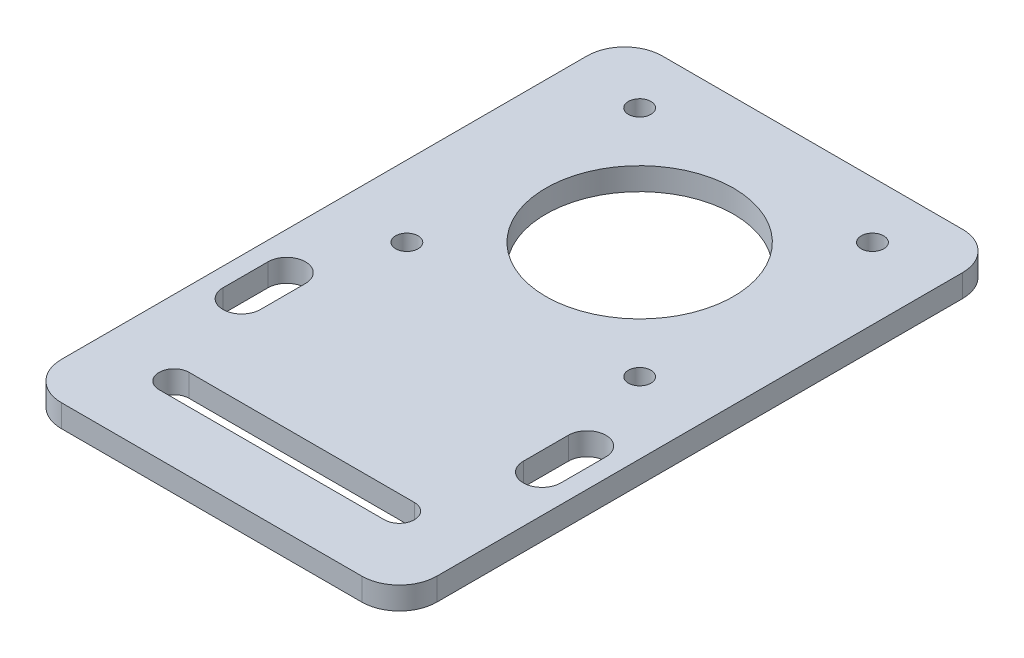
SolidWorks part; units mm, degrees
ref_plane "Front Plane" through (0, 0, 0) normal (0, 0, 1) x (1, 0, 0)
ref_plane "Top Plane" through (0, 0, 0) normal (0, 1, 0) x (1, 0, 0)
ref_plane "Right Plane" through (0, 0, 0) normal (1, 0, 0) x (0, 0, -1)
sketch "Sketch1" plane through (0, 0, 0) normal (0, 1, 0) x (1, 0, 0)
  line L1 (25, 40) -> (-25, 40)
  line L2 (25, 40) -> (25, -40)
  line L3 (25, -40) -> (-25, -40)
  line L4 (-25, 40) -> (-25, -40)
  line L5 (25, 40) -> (-25, -40) construction
  line L6 (25, -40) -> (-25, 40) construction
  point P0 (0, 0)
  dimension "D1" = 50
  dimension "D2" = 80
extrude "Boss-Extrude1" add sketch "Sketch1" along normal blind 3
sketch "Sketch2" plane through (0, 3, 0) normal (0, 1, 0) x (1, 0, 0)
  line L0 (25, 40) -> (-25, 40) construction
  line L1 (-1001.5607, -30) -> (48998.4393, -30) construction
  line L2 (-1001.5607, -40) -> (48998.4393, -40) construction
  line L3 (-15.5, 32.5) -> (15.5, 32.5) construction
  line L4 (-15.5, 32.5) -> (-15.5, 1.5) construction
  line L5 (-15.5, 1.5) -> (15.5, 1.5) construction
  line L6 (15.5, 32.5) -> (15.5, 1.5) construction
  line L7 (-15.5, 32.5) -> (15.5, 1.5) construction
  line L8 (-15.5, 1.5) -> (15.5, 32.5) construction
  line L9 (-1001.5607, -20) -> (48998.4393, -20) construction
  line L10 (-25, -40) -> (25, -40) construction
  line L11 (0, -1000) -> (0, 49000) construction
  line L12 (-15, -30) -> (15, -30) construction
  line L13 (-15, -28) -> (15, -28)
  line L14 (-15, -32) -> (15, -32)
  arc A0 (-15, -28) -> (-15, -32) centre (-15, -30) ccw
  arc A1 (15, -32) -> (15, -28) centre (15, -30) ccw
  circle A2 centre (15.5, 32.5) radius 1.5
  circle A3 centre (-15.5, 32.5) radius 1.5
  circle A4 centre (-15.5, 1.5) radius 1.5
  circle A5 centre (15.5, 1.5) radius 1.5
  circle A6 centre (0, 17) radius 12.5
  point P2 (0, 40)
  point P4 (0, 17)
  point P22 (0, -30)
  dimension "D4" = 2
  dimension "D6" = 3
  dimension "D8" = 25
  dimension "D1" = 31
  dimension "D5" = 30
  dimension "D7" = 23
  dimension "D2" = 10
  dimension "D3" = 10
extrude "Cut-Extrude1" cut sketch "Sketch2" against normal through all
fillet "Fillet1" radius 5 4 edges at (25, 1.5, 40) (-25, 1.5, 40) (-25, 1.5, -40) (25, 1.5, -40)
sketch "Sketch3" plane through (0, 3, 0) normal (0, 1, 0) x (1, 0, 0)
  line L0 (-1017, -30) -> (48983, -30) construction
  line L1 (-1017, -20) -> (48983, -20) construction
  line L2 (0, -1000) -> (0, 49000) construction
  line L3 (-20, -10) -> (-20, -16) construction
  line L4 (20, -10) -> (20, -16) construction
  line L5 (22.5, -10) -> (22.5, -16)
  line L6 (17.5, -10) -> (17.5, -16)
  line L7 (-22.5, -10) -> (-22.5, -16)
  line L8 (-17.5, -10) -> (-17.5, -16)
  arc A0 (-15, -28) -> (-15, -32) centre (-15, -30) ccw construction
  arc A3 (22.5, -10) -> (17.5, -10) centre (20, -10) ccw
  arc A4 (17.5, -16) -> (22.5, -16) centre (20, -16) ccw
  arc A5 (-22.5, -10) -> (-17.5, -10) centre (-20, -10) cw
  arc A6 (-17.5, -16) -> (-22.5, -16) centre (-20, -16) cw
  point P6 (-17, -30)
  point P14 (-20, -13)
  point P15 (20, -13)
  dimension "D2" = 20
  dimension "D4" = 6
  dimension "D5" = 2.5
  dimension "D3" = 10
  dimension "D1" = 10
extrude "Cut-Extrude2" cut sketch "Sketch3" against normal through all
